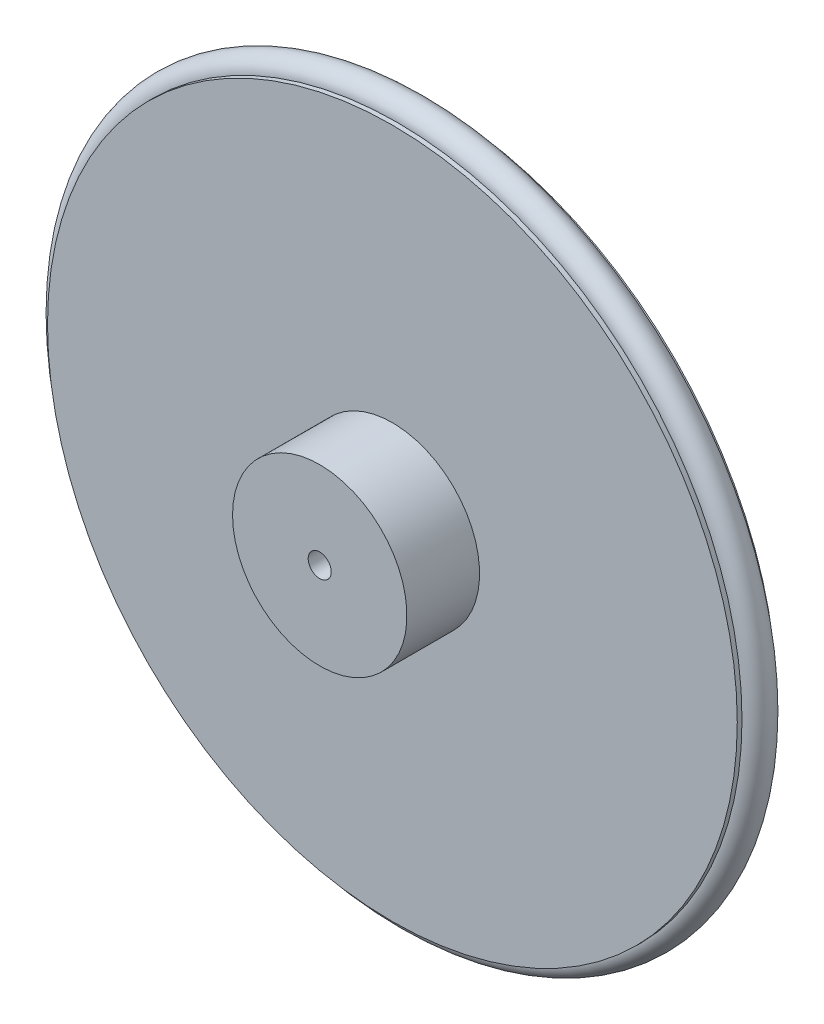
SolidWorks part; units mm, degrees
ref_plane "Plan de face" through (0, 0, 0) normal (0, 0, 1) x (1, 0, 0)
ref_plane "Plan de dessus" through (0, 0, 0) normal (0, 1, 0) x (1, 0, 0)
ref_plane "Plan de droite" through (0, 0, 0) normal (1, 0, 0) x (0, 0, -1)
sketch "Esquisse1" plane through (0, 0, 0) normal (0, 1, 0) x (1, 0, 0)
  line L0 (29.9, 17.3037) -> (29.9, 17.7137)
  line L1 (1, 8.0137) -> (7.5587, 8.0137)
  line L2 (0, 20.0286) -> (0, 2.4359) construction
  line L3 (1, 6.0137) -> (1, 13.0137) construction
  line L4 (7.5587, 8.0137) -> (7.5587, 14.3137)
  line L5 (7.5587, 14.3137) -> (29.9, 14.3137)
  line L6 (0, 17.0529) -> (0, 17.7137)
  line L7 (0, 17.7137) -> (29.9, 17.7137)
  line L8 (29.9, 14.3137) -> (29.9, 14.7237)
  line L9 (0, 17.0529) -> (1, 17.0529)
  line L12 (1, 17.0529) -> (1, 8.0137)
  arc A0 (29.9, 14.7237) -> (29.9, 17.3037) centre (29.9, 16.0137) ccw
  dimension "D3" = 2.58
  dimension "D1" = 3.4
  dimension "D2" = 6.3
  dimension "D4" = 29.9
revolve "Révolution1" add sketch "Esquisse1" angle 360 about L2
